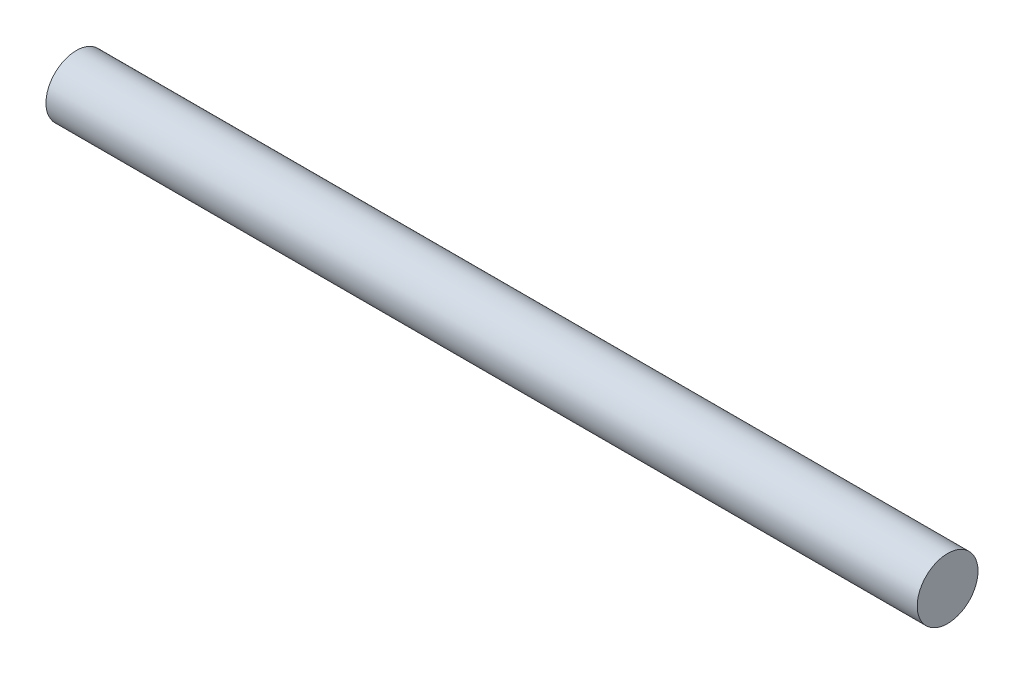
SolidWorks part; units mm, degrees
ref_plane "Plan de face" through (0, 0, 0) normal (0, 0, 1) x (1, 0, 0)
ref_plane "Plan de dessus" through (0, 0, 0) normal (0, 1, 0) x (1, 0, 0)
ref_plane "Plan de droite" through (0, 0, 0) normal (1, 0, 0) x (0, 0, -1)
sketch "Esquisse1" plane through (0, 0, 0) normal (1, 0, 0) x (0, 0, -1)
  circle A0 centre (0, 0) radius 15
  dimension "D1" = 30
extrude "Boss.-Extru.1" add sketch "Esquisse1" along normal blind 430
